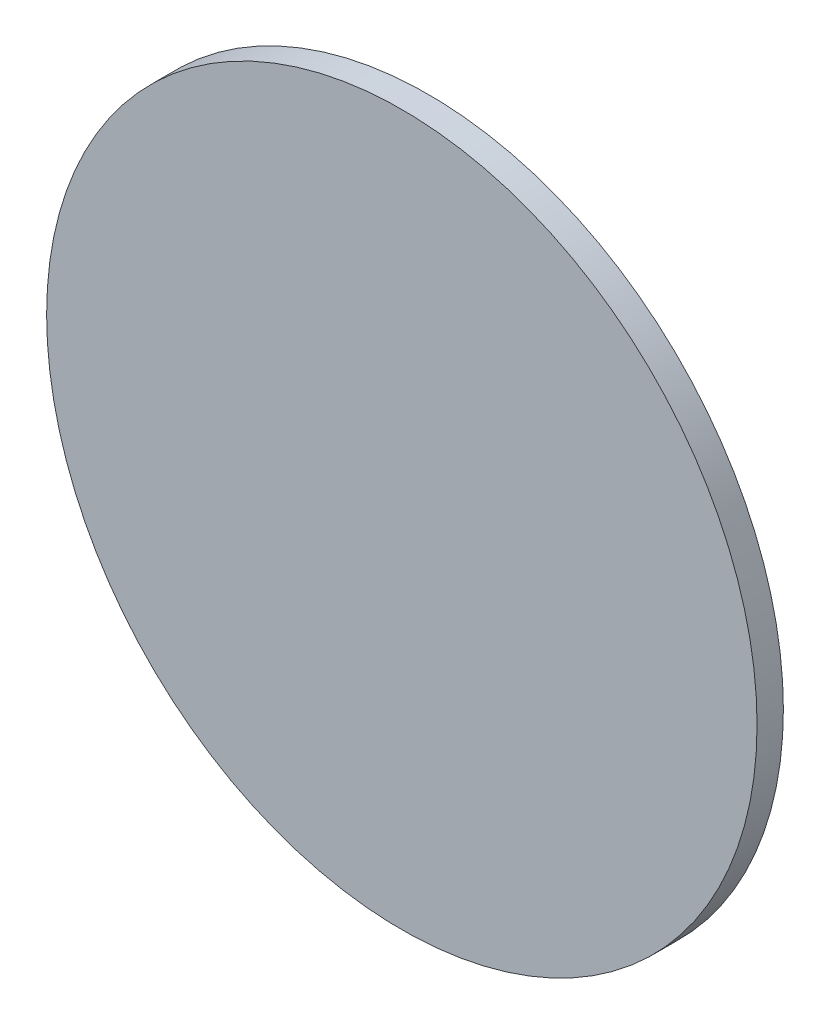
SolidWorks part; units mm, degrees
material "7075-O (SS)"
ref_plane "Front" through (0, 0, 0) normal (0, 0, 1) x (1, 0, 0)
ref_plane "Top" through (0, 0, 0) normal (0, 1, 0) x (1, 0, 0)
ref_plane "Right" through (0, 0, 0) normal (1, 0, 0) x (0, 0, -1)
sketch "Croquis1" plane through (0, 0, 0) normal (0, 0, 1) x (1, 0, 0)
  circle A0 centre (0, 0) radius 67.5
  dimension "D1" = 135
extrude "Saliente-Extruir1" add sketch "Croquis1" along normal blind 5
